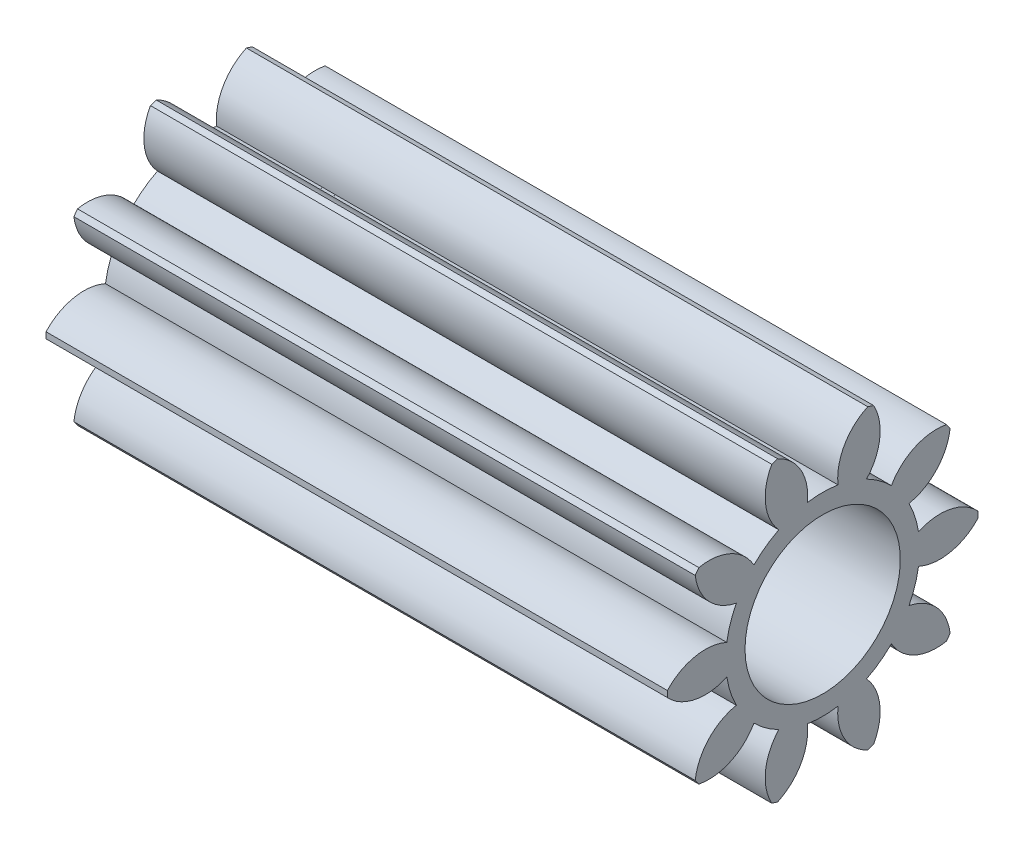
SolidWorks part; units mm, degrees
ref_plane "Plane1" through (0, 0, 0) normal (0, 0, 1) x (1, 0, 0)
ref_plane "Plane2" through (0, 0, 0) normal (0, 1, 0) x (1, 0, 0)
ref_plane "Plane3" through (0, 0, 0) normal (1, 0, 0) x (0, 0, -1)
other "Configuration Table"
sketch "HoldingSke" plane through (0, 0, 0) normal (0, 1, 0) x (1, 0, 0)
  line L0 (0, 0) -> (1.9696, -0.3473)
  line L1 (-15, 0) -> (100, 0) construction
  line L2 (0, 0) -> (-2.1039, 2.3779)
  line L3 (0, 0) -> (-11.863, 4.5341)
  line L4 (0, 0) -> (8.5048, 1.4996)
  line L5 (0, 0) -> (-46.8476, -17.4728)
  line L6 (0, 0) -> (-9.9476, -6.7116)
  line L7 (-2.1039, 2.3779) -> (8.6586, 51.2059)
  line L8 (-76.2, 54.61) -> (-75.7, 54.61)
  line L9 (-71.009, 38.7566) -> (-53.1078, 45.2721)
  line L10 (-76.2, 71.12) -> (104.1128, 71.12)
  line L11 (0, 0) -> (-12, 0)
  line L12 (-76.2, 101.6) -> (-76.181, 101.6)
  line L13 (24.9733, 27.94) -> (52.9518, 28.4284)
  line L14 (24.9733, 27.94) -> (24.9743, 27.94)
  line L15 (24.9733, 27.94) -> (100.4006, 29.5858)
  line L16 (-63.627, -0.5) -> (-12.827, -0.5)
  circle A0 centre (0, 0) radius 1.5
  circle A1 centre (0, 0) radius 1.874
  circle A2 centre (0, 0) radius 37.5
  circle A3 centre (0, 0) radius 1.5
  dimension "MHD" = 3.748
  dimension "Hub_dia" = 75
  dimension "Bore" = 3
  dimension "MBD" = 3
  dimension "Num_teeth" = 10
  dimension "Pitch" = 2
  dimension "Overall_len" = 50
  dimension "Show_teeth" = 10
  dimension "Thickness" = 12
  dimension "OAL" = 50.0001
  dimension "T_dim" = 0.5
  dimension "Ap" = 20
  dimension "H" = 19.05
  dimension "Pitch_radius" = 180.3128
  dimension "Width" = 12
  dimension "Backlash" = 0.019
  dimension "Addendum_fac" = 1
  dimension "Dedendum_fac" = 1.25
  dimension "Clearance_fac" = 0.25
  dimension "Dedendum_add" = 0.001
  dimension "Module" = 0.5
sketch "BasProSke" plane through (0, 0, 0) normal (0, 1, 0) x (1, 0, 0)
  line L0 (-10, 0) -> (60, 0) construction
  line L1 (0, 0) -> (0, 3)
  line L2 (0, 0) -> (12, 0)
  line L3 (12, 0) -> (12, 3)
  line L4 (12, 3) -> (0, 3)
  dimension "Thickness" = 12
  dimension "Diameter" = 6
revolve "Base-Revolve" add sketch "BasProSke" angle 360 about L0
sketch "TooCutSke" plane through (0, 0, 0) normal (1, 0, 0) x (0, 0, -1)
  line L1 (0, 0) -> (0, 107) construction
  line L2 (0, 0) -> (-0.4243, 2.4637) construction
  line L3 (0, 0) -> (-1.5292, 4.7063) construction
  line L4 (-0.4243, 2.4637) -> (-0.7646, 2.3532) construction
  arc A0 (0.2964, 1.8504) -> (-0.2964, 1.8504) centre (0, 0) ccw
  arc A1 (0.9059, 2.8866) -> (-0.9059, 2.8866) centre (0, 0) ccw
  circle A2 centre (0, 0) radius 2.5 construction
  circle A3 centre (0, 0) radius 2.3492 construction
  arc A4 (-0.2964, 1.8504) -> (-0.9059, 2.8866) centre (-1.2901, 1.9633) ccw
  arc A5 (0.9059, 2.8866) -> (0.2964, 1.8504) centre (1.2901, 1.9633) ccw
  dimension "Root_dia" = 3.748
  dimension "Overcut_dia" = 6.0508
  dimension "Pitch_dia" = 5
  dimension "Base_dia" = 4.6985
  dimension "Flank_rad" = 1
  dimension "Half_ang" = 18
  dimension "Half_CT" = 0.3578
extrude "ToothCut" cut sketch "TooCutSke" along normal through all
fillet "Breaks" [suppressed] radius 0.01
fillet "RootFillets" [suppressed] radius 0.126
pattern_circular "TeethCuts" count 10 every 36 about axis through (-10, 0, 0) along (1, 0, 0) of "ToothCut", "RootFillets", "Breaks"
sketch "HubNeaOneSke" plane through (0, 0, 0) normal (-1, 0, 0) x (0, 0, 1)
  circle A0 centre (0, 0) radius 1.874
  dimension "Diameter" = 3.748
extrude "HubNearOne" [suppressed] add sketch "HubNeaOneSke" along normal blind 38.0001
sketch "HubNeaBotSke" plane through (0, 0, 0) normal (-1, 0, 0) x (0, 0, 1)
  circle A0 centre (0, 0) radius 1.874
  dimension "Diameter" = 3.748
extrude "HubNearBoth" [suppressed] add sketch "HubNeaBotSke" along normal blind 19
ref_plane "FarPln" through (12, 0, 0) normal (1, 0, 0) x (0, 0, -1)
sketch "HubFarSke" plane through (12, 0, 0) normal (1, 0, 0) x (0, 0, -1)
  circle A0 centre (0, 0) radius 1.874
  dimension "Diameter" = 3.748
extrude "HubFar" [suppressed] add sketch "HubFarSke" along normal blind 19
sketch "BorSke" plane through (0, 0, 0) normal (1, 0, 0) x (0, 0, -1)
  circle A0 centre (0, 0) radius 1.5
  dimension "Diameter" = 3
extrude "Bore" cut sketch "BorSke" along normal mid plane 100.0001
sketch "KeySke" plane through (0, 0, 0) normal (1, 0, 0) x (0, 0, -1)
  line L0 (-0.6, 0) -> (-0.6, 2)
  line L1 (-0.6, 2) -> (0.6, 2)
  line L2 (0.6, 2) -> (0.6, 0)
  line L3 (0, 0) -> (0, 34) construction
  line L4 (-0.6, 0) -> (0.6, 0)
  dimension "Offset" = 2
extrude "Keyway" [suppressed] cut sketch "KeySke" along normal mid plane 100.0001
pattern_circular "Keyway2" [suppressed] count 2 every 90 about axis through (-10, 0, 0) along (1, 0, 0)
equation "' \"Module@HoldingSke\" = 6.35"
equation "' \"Num_teeth@HoldingSke\" = 12"
equation "' \"Ap@HoldingSke\" =  20"
equation "' \"Ap@HoldingSke\" = 20"
equation "' \"Width@HoldingSke\" = 0.5 * 25.4"
equation "' \"Hub_dia@HoldingSke\"= 1 * 25.4"
equation "' \"Hub_dia@HoldingSke\" = 1 * 25.4"
equation "' \"Overall_len@HoldingSke\" = 1.0 * 25.4"
equation "' \"Bore@HoldingSke\" = 0.75 * 25.4"
equation "' \"T_dim@HoldingSke\" = 0.1 * 25.4"
equation "' \"Width@KeySke\" = 0.25 * 25.4"
equation "' \"Show_teeth@HoldingSke\" = 13"
equation "' \"Backlash@HoldingSke\" = 0.009 * 25.4"
equation "' \"Addendum_fac@HoldingSke\" = 1.0"
equation "' \"Dedendum_fac@HoldingSke\" = 1.25"
equation "' \"Dedendum_add@HoldingSke\" = 0.00005 * 25.4"
equation "' \"Clearance_fac@HoldingSke\" = 0.25"
equation "\"Pitch@HoldingSke\" = 1 / \"Module@HoldingSke\""
equation "\"Overcut_dia@TooCutSke\" = (\"Num_teeth@HoldingSke\" + 2 * \"Addendum_fac@HoldingSke\") / \"Pitch@HoldingSke\" + 0.002 * 25.4"
equation "\"Pitch_dia@TooCutSke\" = \"Num_teeth@HoldingSke\" / \"Pitch@HoldingSke\""
equation "\"Base_dia@TooCutSke\" = \"Num_teeth@HoldingSke\" / \"Pitch@HoldingSke\" * cos((\"Ap@HoldingSke\"  * 3.14159265 / 180))"
equation "\"Root_dia@TooCutSke\" = (\"Num_teeth@HoldingSke\" + 2) / \"Pitch@HoldingSke\" - 2 * (\"Addendum_fac@HoldingSke\" + \"Dedendum_fac@HoldingSke\") / \"Pitch@HoldingSke\" - \"Dedendum_add@HoldingSke\" * 2"
equation "\"Half_ang@TooCutSke\" = 180 / \"Num_teeth@HoldingSke\""
equation "\"Half_CT@TooCutSke\" = \"Num_teeth@HoldingSke\" / \"Pitch@HoldingSke\" * sin((3.14159265 / 2 / \"Num_teeth@HoldingSke\")) / 2 - 7 * \"Backlash@HoldingSke\" / 4"
equation "\"Flank_rad@TooCutSke\" = \"Num_teeth@HoldingSke\" / \"Pitch@HoldingSke\" / 5"
equation "\"Radius@RootFillets\" = \"Clearance_fac@HoldingSke\" / \"Pitch@HoldingSke\" + \"Dedendum_add@HoldingSke\""
equation "\"Break_rad@Breaks\" = 0.02 / \"Pitch@HoldingSke\""
equation "\"Thickness@HoldingSke\" = \"Width@HoldingSke\""
equation "\"OAL@HoldingSke\" = \"Thickness@HoldingSke\""
equation "\"MHD@HoldingSke\" = (\"Num_teeth@HoldingSke\" + 2) / \"Pitch@HoldingSke\" - 2 * (\"Addendum_fac@HoldingSke\" + \"Dedendum_fac@HoldingSke\")  / \"Pitch@HoldingSke\" - \"Dedendum_add@HoldingSke\" * 2"
equation "\"MBD@HoldingSke\" = (\"Num_teeth@HoldingSke\" + 2) / \"Pitch@HoldingSke\" - 2 * (\"Addendum_fac@HoldingSke\" + \"Dedendum_fac@HoldingSke\")  / \"Pitch@HoldingSke\" - \"Dedendum_add@HoldingSke\" * 2 - 0.002 * 25.4"
equation "\"MHD@HoldingSke\" = ((sgn( \"MHD@HoldingSke\" - \"Hub_dia@HoldingSke\" )-1)*( \"MHD@HoldingSke\" - \"Hub_dia@HoldingSke\" ))/-2+ \"Hub_dia@HoldingSke\""
equation "\"MBD@HoldingSke\" = ((sgn( \"MBD@HoldingSke\" - \"Bore@HoldingSke\" )-1)*( \"MBD@HoldingSke\" - \"Bore@HoldingSke\" ))/-2+ \"Bore@HoldingSke\""
equation "\"OAL@HoldingSke\" = ((sgn( \"OAL@HoldingSke\" - \"Overall_len@HoldingSke\" )+1)*( \"OAL@HoldingSke\" - \"Overall_len@HoldingSke\" ))/2 + \"Overall_len@HoldingSke\" + 0.000002 * 25.4"
equation "\"Num_teeth@TeethCuts\" = int( \"Show_teeth@HoldingSke\" ) + 1"
equation "\"Num_teeth@TeethCuts\" = ((sgn( \"Num_teeth@TeethCuts\" - \"Num_teeth@HoldingSke\" )-1)*( \"Num_teeth@TeethCuts\" - \"Num_teeth@HoldingSke\" ))/-2+ \"Num_teeth@HoldingSke\""
equation "\"Num_teeth@TeethCuts\" = ((sgn( \"Num_teeth@TeethCuts\" - 2.0)+1)*( \"Num_teeth@TeethCuts\" - 2.0))/2 +2.0"
equation "\"Angle@TeethCuts\" = 360.0 / \"Num_teeth@HoldingSke\""
equation "\"Diameter@BasProSke\" = (\"Num_teeth@HoldingSke\" + 2 * \"Addendum_fac@HoldingSke\") / \"Pitch@HoldingSke\""
equation "\"Thickness@BasProSke\"  = \"Thickness@HoldingSke\""
equation "' \"Fillet_rad@BasProSke\" =  \"Thickness@HoldingSke\" * 0.05"
equation "' \"Fillet_rad@BasProSke\" = \"Thickness@HoldingSke\" * 0.05"
equation "\"MHD@HoldingSke\" = ((sgn( \"MHD@HoldingSke\" - \"Root_dia@TooCutSke\" )-1)*( \"MHD@HoldingSke\" - \"Root_dia@TooCutSke\" ))/-2+ \"Root_dia@TooCutSke\""
equation "\"Diameter@HubNeaOneSke\" = \"MHD@HoldingSke\""
equation "\"Length@HubNearOne\" = \"OAL@HoldingSke\" - \"Thickness@BasProSke\""
equation "\"Diameter@HubNeaBotSke\" = \"MHD@HoldingSke\""
equation "\"Length@HubNearBoth\" = ( \"OAL@HoldingSke\" - \"Thickness@BasProSke\" ) / 2.0"
equation "\"Thickness@FarPln\" = \"Thickness@BasProSke\""
equation "\"Diameter@HubFarSke\" = \"MHD@HoldingSke\""
equation "\"Length@HubFar\" = ( \"OAL@HoldingSke\" - \"Thickness@BasProSke\" ) / 2.0"
equation "\"Diameter@BorSke\" = \"MBD@HoldingSke\""
equation "\"D1@Bore\" = \"OAL@HoldingSke\" * 2.0"
equation "\"D1@Keyway\" = \"OAL@HoldingSke\" * 2.0"
equation "\"Offset@KeySke\" = \"T_dim@HoldingSke\" + \"MBD@HoldingSke\" / 2.0"
